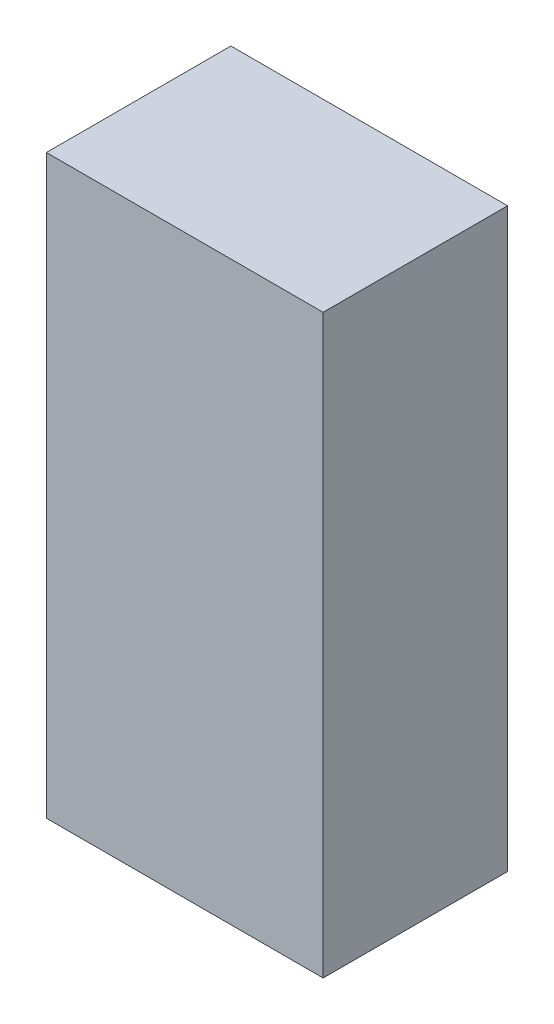
SolidWorks part; units mm, degrees
ref_plane "Front Plane" through (0, 0, 0) normal (0, 0, 1) x (1, 0, 0)
ref_plane "Top Plane" through (0, 0, 0) normal (0, 1, 0) x (1, 0, 0)
ref_plane "Right Plane" through (0, 0, 0) normal (1, 0, 0) x (0, 0, -1)
sketch "Sketch1" plane through (0, 0, 0) normal (0, 0, 1) x (1, 0, 0)
  line L1 (-6, -12.5) -> (6, -12.5)
  line L2 (-6, -12.5) -> (-6, 12.5)
  line L3 (-6, 12.5) -> (6, 12.5)
  line L4 (6, -12.5) -> (6, 12.5)
  line L5 (-6, -12.5) -> (6, 12.5) construction
  line L6 (-6, 12.5) -> (6, -12.5) construction
  point P0 (0, 0)
extrude "Envelope" add sketch "Sketch1" along normal blind 8
